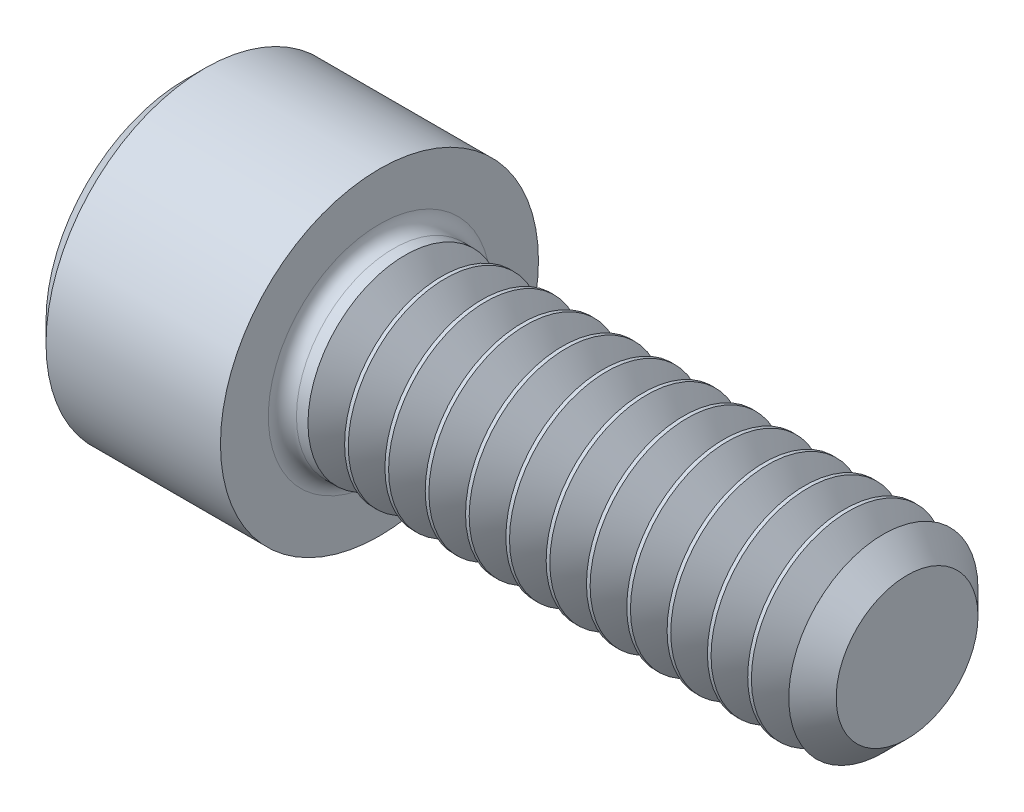
SolidWorks part; units mm, degrees
material "Chrome Stainless Steel"
ref_plane "Front Plane" through (0, 0, 0) normal (0, 0, 1) x (1, 0, 0)
ref_plane "Top Plane" through (0, 0, 0) normal (0, 1, 0) x (1, 0, 0)
ref_plane "Right Plane" through (0, 0, 0) normal (1, 0, 0) x (0, 0, -1)
ref_plane "Plane1" through (0, 0, 0) normal (0, 0, -1) x (-1, 0, 0)
sketch "Sketch1" plane through (0, 0, 0) normal (0, 0, -1) x (-1, 0, 0)
  line L0 (-3.5052, 2.8702) -> (-3.5052, 0)
  line L1 (-3.5052, 0) -> (0, 0)
  line L2 (0, 0) -> (0, 2.8702)
  line L3 (0, 2.8702) -> (-3.5052, 2.8702)
  line L4 (-3.5052, 0) -> (0, 0) construction
revolve "Revolve1" add sketch "Sketch1" angle 360 about L4
sketch "Sketch2" plane through (3.5052, 0, 0) normal (1, 0, 0) x (0, 0, -1)
  circle A0 centre (0, 0) radius 1.7526
extrude "Boss-Extrude1" add sketch "Sketch2" along normal blind 0.4617
sketch "Sketch3" plane through (3.9669, 0, 0) normal (1, 0, 0) x (0, 0, -1)
  circle A0 centre (0, 0) radius 1.7526
extrude "Boss-Extrude2" add sketch "Sketch3" along normal blind 0.3308 draft 55
sketch "Sketch4" plane through (4.2977, 0, 0) normal (1, 0, 0) x (0, 0, -1)
  circle A0 centre (0, 0) radius 1.2802
extrude "Boss-Extrude3" add sketch "Sketch4" along normal blind 0.3308 draft 55 draft outward yes
sketch "Sketch5" plane through (4.6285, 0, 0) normal (1, 0, 0) x (0, 0, -1)
  circle A0 centre (0, 0) radius 1.7526
extrude "Boss-Extrude4" add sketch "Sketch5" along normal blind 0.0661
sketch "Sketch6" plane through (4.6946, 0, 0) normal (1, 0, 0) x (0, 0, -1)
  circle A0 centre (0, 0) radius 1.7526
extrude "Boss-Extrude5" add sketch "Sketch6" along normal blind 0.3308 draft 55
sketch "Sketch7" plane through (5.0254, 0, 0) normal (1, 0, 0) x (0, 0, -1)
  circle A0 centre (0, 0) radius 1.2802
extrude "Boss-Extrude6" add sketch "Sketch7" along normal blind 0.3308 draft 55 draft outward yes
sketch "Sketch8" plane through (5.3562, 0, 0) normal (1, 0, 0) x (0, 0, -1)
  circle A0 centre (0, 0) radius 1.7526
extrude "Boss-Extrude7" add sketch "Sketch8" along normal blind 0.0661
sketch "Sketch9" plane through (5.4223, 0, 0) normal (1, 0, 0) x (0, 0, -1)
  circle A0 centre (0, 0) radius 1.7526
extrude "Boss-Extrude8" add sketch "Sketch9" along normal blind 0.3308 draft 55
sketch "Sketch10" plane through (5.7531, 0, 0) normal (1, 0, 0) x (0, 0, -1)
  circle A0 centre (0, 0) radius 1.2802
extrude "Boss-Extrude9" add sketch "Sketch10" along normal blind 0.3308 draft 55 draft outward yes
sketch "Sketch11" plane through (6.0839, 0, 0) normal (1, 0, 0) x (0, 0, -1)
  circle A0 centre (0, 0) radius 1.7526
extrude "Boss-Extrude10" add sketch "Sketch11" along normal blind 0.0661
sketch "Sketch12" plane through (6.15, 0, 0) normal (1, 0, 0) x (0, 0, -1)
  circle A0 centre (0, 0) radius 1.7526
extrude "Boss-Extrude11" add sketch "Sketch12" along normal blind 0.3308 draft 55
sketch "Sketch13" plane through (6.4808, 0, 0) normal (1, 0, 0) x (0, 0, -1)
  circle A0 centre (0, 0) radius 1.2802
extrude "Boss-Extrude12" add sketch "Sketch13" along normal blind 0.3308 draft 55 draft outward yes
sketch "Sketch14" plane through (6.8116, 0, 0) normal (1, 0, 0) x (0, 0, -1)
  circle A0 centre (0, 0) radius 1.7526
extrude "Boss-Extrude13" add sketch "Sketch14" along normal blind 0.0661
sketch "Sketch15" plane through (6.8777, 0, 0) normal (1, 0, 0) x (0, 0, -1)
  circle A0 centre (0, 0) radius 1.7526
extrude "Boss-Extrude14" add sketch "Sketch15" along normal blind 0.3308 draft 55
sketch "Sketch16" plane through (7.2085, 0, 0) normal (1, 0, 0) x (0, 0, -1)
  circle A0 centre (0, 0) radius 1.2802
extrude "Boss-Extrude15" add sketch "Sketch16" along normal blind 0.3308 draft 55 draft outward yes
sketch "Sketch17" plane through (7.5393, 0, 0) normal (1, 0, 0) x (0, 0, -1)
  circle A0 centre (0, 0) radius 1.7526
extrude "Boss-Extrude16" add sketch "Sketch17" along normal blind 0.0661
sketch "Sketch18" plane through (7.6054, 0, 0) normal (1, 0, 0) x (0, 0, -1)
  circle A0 centre (0, 0) radius 1.7526
extrude "Boss-Extrude17" add sketch "Sketch18" along normal blind 0.3308 draft 55
sketch "Sketch19" plane through (7.9362, 0, 0) normal (1, 0, 0) x (0, 0, -1)
  circle A0 centre (0, 0) radius 1.2802
extrude "Boss-Extrude18" add sketch "Sketch19" along normal blind 0.3308 draft 55 draft outward yes
sketch "Sketch20" plane through (8.267, 0, 0) normal (1, 0, 0) x (0, 0, -1)
  circle A0 centre (0, 0) radius 1.7526
extrude "Boss-Extrude19" add sketch "Sketch20" along normal blind 0.0661
sketch "Sketch21" plane through (8.3331, 0, 0) normal (1, 0, 0) x (0, 0, -1)
  circle A0 centre (0, 0) radius 1.7526
extrude "Boss-Extrude20" add sketch "Sketch21" along normal blind 0.3308 draft 55
sketch "Sketch22" plane through (8.6639, 0, 0) normal (1, 0, 0) x (0, 0, -1)
  circle A0 centre (0, 0) radius 1.2802
extrude "Boss-Extrude21" add sketch "Sketch22" along normal blind 0.3308 draft 55 draft outward yes
sketch "Sketch23" plane through (8.9947, 0, 0) normal (1, 0, 0) x (0, 0, -1)
  circle A0 centre (0, 0) radius 1.7526
extrude "Boss-Extrude22" add sketch "Sketch23" along normal blind 0.0661
sketch "Sketch24" plane through (9.0608, 0, 0) normal (1, 0, 0) x (0, 0, -1)
  circle A0 centre (0, 0) radius 1.7526
extrude "Boss-Extrude23" add sketch "Sketch24" along normal blind 0.3308 draft 55
sketch "Sketch25" plane through (9.3916, 0, 0) normal (1, 0, 0) x (0, 0, -1)
  circle A0 centre (0, 0) radius 1.2802
extrude "Boss-Extrude24" add sketch "Sketch25" along normal blind 0.3308 draft 55 draft outward yes
sketch "Sketch26" plane through (9.7225, 0, 0) normal (1, 0, 0) x (0, 0, -1)
  circle A0 centre (0, 0) radius 1.7526
extrude "Boss-Extrude25" add sketch "Sketch26" along normal blind 0.0661
sketch "Sketch27" plane through (9.7886, 0, 0) normal (1, 0, 0) x (0, 0, -1)
  circle A0 centre (0, 0) radius 1.7526
extrude "Boss-Extrude26" add sketch "Sketch27" along normal blind 0.3308 draft 55
sketch "Sketch28" plane through (10.1194, 0, 0) normal (1, 0, 0) x (0, 0, -1)
  circle A0 centre (0, 0) radius 1.2802
extrude "Boss-Extrude27" add sketch "Sketch28" along normal blind 0.3308 draft 55 draft outward yes
sketch "Sketch29" plane through (10.4502, 0, 0) normal (1, 0, 0) x (0, 0, -1)
  circle A0 centre (0, 0) radius 1.7526
extrude "Boss-Extrude28" add sketch "Sketch29" along normal blind 0.0661
sketch "Sketch30" plane through (10.5163, 0, 0) normal (1, 0, 0) x (0, 0, -1)
  circle A0 centre (0, 0) radius 1.7526
extrude "Boss-Extrude29" add sketch "Sketch30" along normal blind 0.3308 draft 55
sketch "Sketch31" plane through (10.8471, 0, 0) normal (1, 0, 0) x (0, 0, -1)
  circle A0 centre (0, 0) radius 1.2802
extrude "Boss-Extrude30" add sketch "Sketch31" along normal blind 0.3308 draft 55 draft outward yes
sketch "Sketch32" plane through (11.1779, 0, 0) normal (1, 0, 0) x (0, 0, -1)
  circle A0 centre (0, 0) radius 1.7526
extrude "Boss-Extrude31" add sketch "Sketch32" along normal blind 0.0661
sketch "Sketch33" plane through (11.244, 0, 0) normal (1, 0, 0) x (0, 0, -1)
  circle A0 centre (0, 0) radius 1.7526
extrude "Boss-Extrude32" add sketch "Sketch33" along normal blind 0.3308 draft 55
sketch "Sketch34" plane through (11.5748, 0, 0) normal (1, 0, 0) x (0, 0, -1)
  circle A0 centre (0, 0) radius 1.2802
extrude "Boss-Extrude33" add sketch "Sketch34" along normal blind 0.3308 draft 55 draft outward yes
sketch "Sketch35" plane through (11.9056, 0, 0) normal (1, 0, 0) x (0, 0, -1)
  circle A0 centre (0, 0) radius 1.7526
extrude "Boss-Extrude34" add sketch "Sketch35" along normal blind 0.0661
sketch "Sketch36" plane through (11.9717, 0, 0) normal (1, 0, 0) x (0, 0, -1)
  circle A0 centre (0, 0) radius 1.7526
extrude "Boss-Extrude35" add sketch "Sketch36" along normal blind 0.3308 draft 55
sketch "Sketch37" plane through (12.3025, 0, 0) normal (1, 0, 0) x (0, 0, -1)
  circle A0 centre (0, 0) radius 1.2802
extrude "Boss-Extrude36" add sketch "Sketch37" along normal blind 0.2997 draft 55 draft outward yes
sketch "Sketch38" plane through (12.6022, 0, 0) normal (1, 0, 0) x (0, 0, -1)
  circle A0 centre (0, 0) radius 1.7082
extrude "Boss-Extrude37" add sketch "Sketch38" along normal blind 0.428 draft 45
sketch "Sketch39" plane through (0, 0, 0) normal (-1, 0, 0) x (0, 0, 1)
  line L0 (-1.3843, -0.7992) -> (0, -1.5985)
  line L1 (0, -1.5985) -> (1.3843, -0.7992)
  line L2 (1.3843, -0.7992) -> (1.3843, 0.7992)
  line L3 (1.3843, 0.7992) -> (0, 1.5985)
  line L4 (0, 1.5985) -> (-1.3843, 0.7992)
  line L5 (-1.3843, 0.7992) -> (-1.3843, -0.7992)
extrude "Cut-Extrude1" cut sketch "Sketch39" against normal blind 1.6256
sketch "Sketch40" plane through (0, 0, 0) normal (0, 0, 1) x (1, 0, 0)
  line L0 (1.6256, 1.3843) -> (1.6256, 0)
  line L1 (1.6256, 0) -> (2.4248, 0)
  line L2 (2.4248, 0) -> (1.6256, 1.3843)
  line L3 (1.6256, 0) -> (2.4249, 0) construction
revolve "Cut-Revolve1" cut sketch "Sketch40" angle 360 about L3
chamfer "Chamfer1" distance 0.3556 angle 45 1 edges at (0, 0, 2.8702)
fillet "Fillet1" radius 0.254 1 edges at (3.5052, 0, -1.7526)
